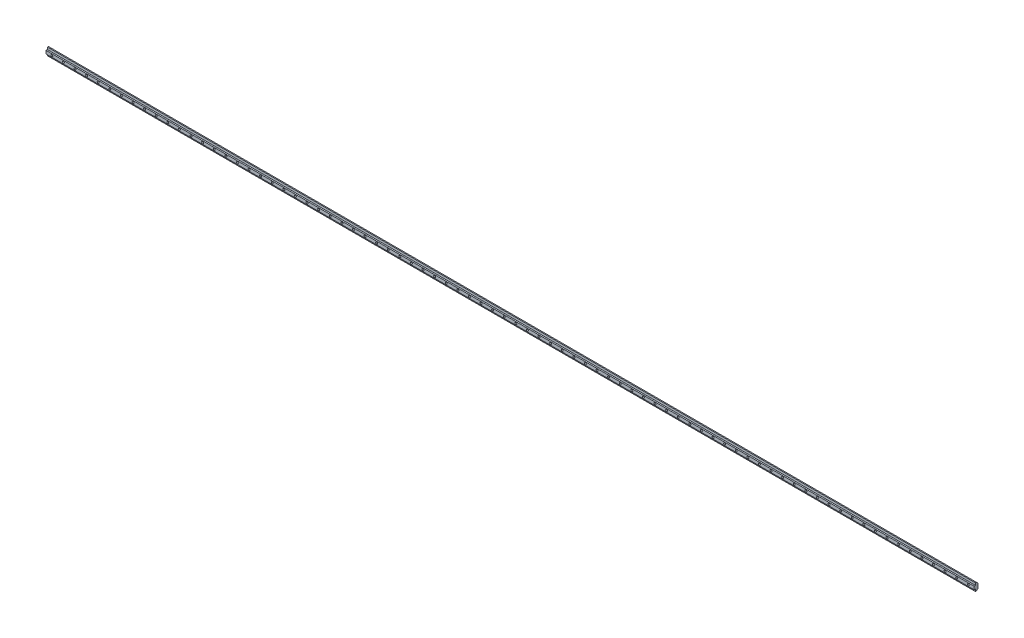
SolidWorks part; units mm, degrees
ref_plane "前视基准面" through (0, 0, 0) normal (0, 0, 1) x (1, 0, 0)
ref_plane "上视基准面" through (0, 0, 0) normal (0, 1, 0) x (1, 0, 0)
ref_plane "右视基准面" through (0, 0, 0) normal (1, 0, 0) x (0, 0, -1)
sketch "草图1" plane through (0, 0, 0) normal (0, 0, 1) x (1, 0, 0)
  line L1 (-1200, -9.8) -> (1200, -9.8)
  line L2 (-1200, -9.8) -> (-1200, 9.8)
  line L3 (-1200, 9.8) -> (1200, 9.8)
  line L4 (1200, -9.8) -> (1200, 9.8)
  line L5 (-1200, -9.8) -> (1200, 9.8) construction
  line L6 (-1200, 9.8) -> (1200, -9.8) construction
  point P0 (0, 0)
  dimension "D1" = 2400
  dimension "D2" = 19.6
extrude "凸台-拉伸1" add sketch "草图1" along normal blind 6.6
sketch "草图2" plane through (0, 0, 6.6) normal (0, 0, 1) x (1, 0, 0)
  line L0 (1200, -9.8) -> (1200, 9.8) construction
  line L1 (-1200, -4.05) -> (1200, -4.05)
  line L2 (-1200, -4.05) -> (-1200, 4.05)
  line L3 (-1200, 4.05) -> (1200, 4.05)
  line L4 (1200, -4.05) -> (1200, 4.05)
  line L5 (-1200, -4.05) -> (1200, 4.05) construction
  line L6 (-1200, 4.05) -> (1200, -4.05) construction
  point P1 (0, 0)
  dimension "D1" = 8.1
extrude "凸台-拉伸2" add sketch "草图2" along normal blind 3.5
chamfer "倒角1" distance 4 angle 45 2 edges at (0, -9.8, 0) (0, 9.8, 0)
hole_wizard "M6 螺纹孔1" positions "草图4" profile "草图3" tap size "M6" standard "GB" end condition through all
sketch "草图4" plane through (0, 0, 10.1) normal (0, 0, 1) x (1, 0, 0)
  line L0 (-1200, 4.05) -> (-1200, -4.05) construction
  point P0 (-1185, 0)
  point P15 (-1200, 0)
  dimension "D1" = 15
sketch "草图3" plane through (-1185, 0, 10.1) normal (1, 0, 0) x (0, -1, 0)
  line L0 (0, 0) -> (0, 10.1)
  line L1 (0, 10.1) -> (2.5, 10.1)
  line L2 (2.5, 10.1) -> (2.5, 0)
  line L5 (2.5, 0) -> (0, 0)
  line L11 (0, -6.35) -> (0, 107.95) construction
  dimension "螺纹线主直径" = 5
  dimension "通孔螺纹孔钻头深度" = 10.1
pattern_linear "阵列(线性)1" count 80 spacing 30 along (1, 0, 0) of "M6 螺纹孔1"
